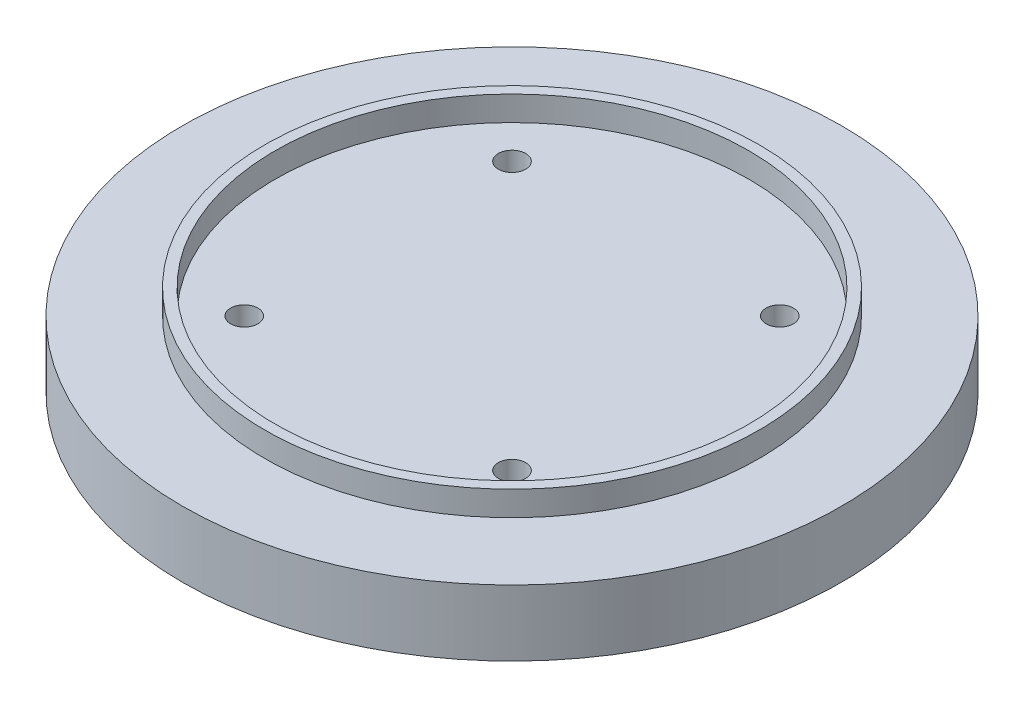
SolidWorks part; units mm, degrees
ref_plane "Front Plane" through (0, 0, 0) normal (0, 0, 1) x (1, 0, 0)
ref_plane "Top Plane" through (0, 0, 0) normal (0, 1, 0) x (1, 0, 0)
ref_plane "Right Plane" through (0, 0, 0) normal (1, 0, 0) x (0, 0, -1)
sketch "Sketch1" plane through (0, 0, 0) normal (0, 1, 0) x (1, 0, 0)
  circle A0 centre (0, 0) radius 101.6
extrude "Boss-Extrude1" add sketch "Sketch1" along normal mid plane 20.32
sketch "Sketch2" plane through (0, 10.16, 0) normal (0, 1, 0) x (1, 0, 0)
  circle A0 centre (0, 0) radius 76.2
  circle A1 centre (0, 0) radius 73.025
hole_wizard "3/8-24 Tapped Hole2" positions "Sketch4" profile "Sketch3" tap size "3/8-24" standard "ANSI Inch"
sketch "Sketch4" plane through (0, 10.16, 0) normal (0, 1, 0) x (1, 0, 0)
  point P0 (-41.275, 41.275)
  point P2 (41.275, 41.275)
  point P4 (41.275, -41.275)
  point P6 (-41.275, -41.275)
  dimension "D1" = 41.275
  dimension "D2" = 41.275
  dimension "D3" = 41.275
  dimension "D4" = 41.275
sketch "Sketch3" plane through (-41.275, 10.16, -41.275) normal (1, 0, 0) x (0, 0, 1)
  line L0 (0, 0) -> (0, 15.9955)
  line L1 (0, 15.9955) -> (4.2164, 13.462)
  line L2 (4.2164, 13.462) -> (4.2164, 0)
  line L5 (4.2164, 0) -> (0, 0)
  line L10 (0, 15.9955) -> (-4.2164, 13.462) construction
  line L11 (0, -6.35) -> (0, 107.95) construction
  dimension "Tap Drill Dia." = 8.4328
  dimension "Tap Drill Depth" = 13.462
  dimension "Drill Angle" = 118
cosmetic thread "Hole Thread1" parameters "D1"=12.192, "D2"=10.5156
cosmetic thread "Hole Thread2" parameters "D1"=12.192, "D2"=10.5156
cosmetic thread "Hole Thread3" parameters "D1"=12.192, "D2"=10.5156
cosmetic thread "Hole Thread4" parameters "D1"=12.192, "D2"=10.5156
hole_wizard "3/8-24 Tapped Hole1" positions "Sketch6" profile "Sketch5" tap size "3/8-24" standard "ANSI Inch"
sketch "Sketch6" plane through (0, -10.16, 0) normal (0, -1, 0) x (-1, 0, 0)
  point P0 (50.8, -50.8)
  point P2 (-50.8, -50.8)
  point P4 (-50.8, 50.8)
  point P6 (50.8, 50.8)
  dimension "D1" = 50.8
  dimension "D2" = 50.8
  dimension "D3" = 50.8
  dimension "D4" = 50.8
sketch "Sketch5" plane through (-50.8, -10.16, 50.8) normal (1, 0, 0) x (0, 0, -1)
  line L0 (0, 0) -> (0, 16.7575)
  line L1 (0, 16.7575) -> (4.2164, 14.224)
  line L2 (4.2164, 14.224) -> (4.2164, 0)
  line L5 (4.2164, 0) -> (0, 0)
  line L10 (0, 16.7575) -> (-4.2164, 14.224) construction
  line L11 (0, -6.35) -> (0, 107.95) construction
  dimension "Tap Drill Dia." = 8.4328
  dimension "Tap Drill Depth" = 14.224
  dimension "Drill Angle" = 118
cosmetic thread "Hole Thread5" parameters "D1"=14.224, "D2"=9.525
cosmetic thread "Hole Thread6" parameters "D1"=14.224, "D2"=9.525
cosmetic thread "Hole Thread7" parameters "D1"=14.224, "D2"=9.525
cosmetic thread "Hole Thread8" parameters "D1"=14.224, "D2"=9.525
extrude "Boss-Extrude2" add sketch "Sketch2" along normal blind 7.62
